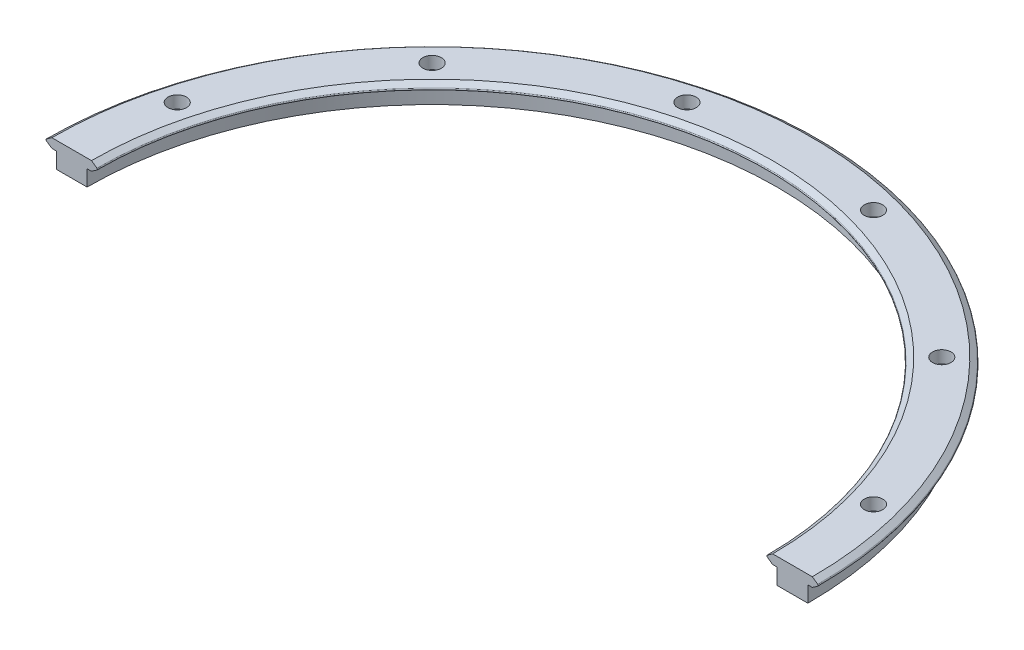
SolidWorks part; units mm, degrees
material "A6061"
ref_plane "前视基准面" through (0, 0, 0) normal (0, 0, 1) x (1, 0, 0)
ref_plane "上视基准面" through (0, 0, 0) normal (0, 1, 0) x (1, 0, 0)
ref_plane "右视基准面" through (0, 0, 0) normal (1, 0, 0) x (0, 0, -1)
sketch "草图1" plane through (0, 0, 0) normal (0, 0, 1) x (1, 0, 0)
  line L0 (185.1567, 2.25) -> (0, 2.25)
  line L1 (0, 2.25) -> (0, -2.25)
  line L2 (0, -2.25) -> (185.1567, -2.25)
  line L3 (185.1567, -2.25) -> (187.7851, -0.4096)
  line L4 (187.7851, 0.4096) -> (185.1567, 2.25)
  line L5 (0, 2.25) -> (0, -2.25) construction
  spline S0 degree 3 poles (187.7851, 0.4096) (187.8309, 0.3775) (187.8718, 0.337) (187.9045, 0.2916) (187.9371, 0.2461) (187.9623, 0.1944) (187.9781, 0.1407) (187.9938, 0.087) (188.0005, 0.0298) (187.9976, -0.0261) (187.9947, -0.082) (187.9821, -0.1381) (187.9608, -0.1899) (187.9396, -0.2417) (187.9091, -0.2905) (187.8719, -0.3323) (187.8461, -0.3612) (187.8168, -0.3874) (187.7851, -0.4096) knots 0 0 0 0 0.000168 0.000168 0.000168 0.000336 0.000336 0.000336 0.000504 0.000504 0.000504 0.000672 0.000672 0.000672 0.000839 0.000839 0.000839 0.000955 0.000955 0.000955 0.000955
revolve "旋转1" add sketch "草图1" angle 360 about L5
sketch "草图2" plane through (0, -2.25, 0) normal (0, -1, 0) x (1, 0, 0)
  circle A0 centre (0, 0) radius 183
extrude "凸台-拉伸1" add sketch "草图2" along normal blind 7.75
sketch "草图3" plane through (0, 0, 0) normal (0, 0, 1) x (1, 0, 0)
  line L0 (165.8433, 2.25) -> (0, 2.25)
  line L1 (0, 2.25) -> (0, -10)
  line L2 (0, -10) -> (168, -10)
  line L3 (168, -10) -> (168, -2.25)
  line L4 (168, -2.25) -> (165.8433, -2.25)
  line L5 (165.8433, -2.25) -> (163.2149, -0.4096)
  line L6 (163.2149, 0.4096) -> (165.8433, 2.25)
  line L7 (0, 2.25) -> (0, -10) construction
  arc A0 (163.2149, -0.4096) -> (163.2149, 0.4096) centre (163.5017, 0) cw
revolve "切除-旋转1" cut sketch "草图3" angle 360 about L7
hole_wizard "M5 六角头螺栓的柱形沉头孔1" positions "草图5" profile "草图4" counterbore size "M5" standard "ANSI Metric"
sketch "草图5" plane through (0, 2.25, 0) normal (0, 1, 0) x (1, 0, 0)
  point P0 (-45.4227, -169.52)
  point P1 (-124.0972, -124.0972)
  point P2 (-169.52, -45.4227)
  point P3 (45.4227, -169.52)
  point P4 (124.0972, -124.0972)
  point P5 (169.52, -45.4227)
  point P6 (-45.4227, 169.52)
  point P7 (-124.0972, 124.0972)
  point P8 (-169.52, 45.4227)
  point P9 (45.4227, 169.52)
  point P10 (124.0972, 124.0972)
  point P11 (169.52, 45.4227)
sketch "草图4" plane through (-45.4227, 2.25, 169.52) normal (1, 0, 0) x (0, 0, 1)
  line L0 (0, 0) -> (0, 12.25)
  line L1 (0, 12.25) -> (2.75, 12.25)
  line L3 (2.75, 12.25) -> (2.75, 6)
  line L4 (2.75, 6) -> (4.5, 6)
  line L5 (4.5, 6) -> (4.5, 0)
  line L7 (4.5, 0) -> (0, 0)
  line L11 (0, -6.35) -> (0, 107.95) construction
  dimension "通孔孔直径" = 5.5
  dimension "通孔孔深度" = 12.25
  dimension "柱形沉头孔直径" = 9
  dimension "柱形沉头孔深度" = 6
sketch "草图6" plane through (0, 2.25, 0) normal (0, 1, 0) x (1, 0, 0)
  line L1 (-255.1095, 0) -> (244.8021, 0)
  line L2 (-255.1095, 0) -> (-255.1095, -215.3522)
  line L3 (-255.1095, -215.3522) -> (244.8021, -215.3522)
  line L4 (244.8021, 0) -> (244.8021, -215.3522)
extrude "切除-拉伸1" cut sketch "草图6" against normal through all
